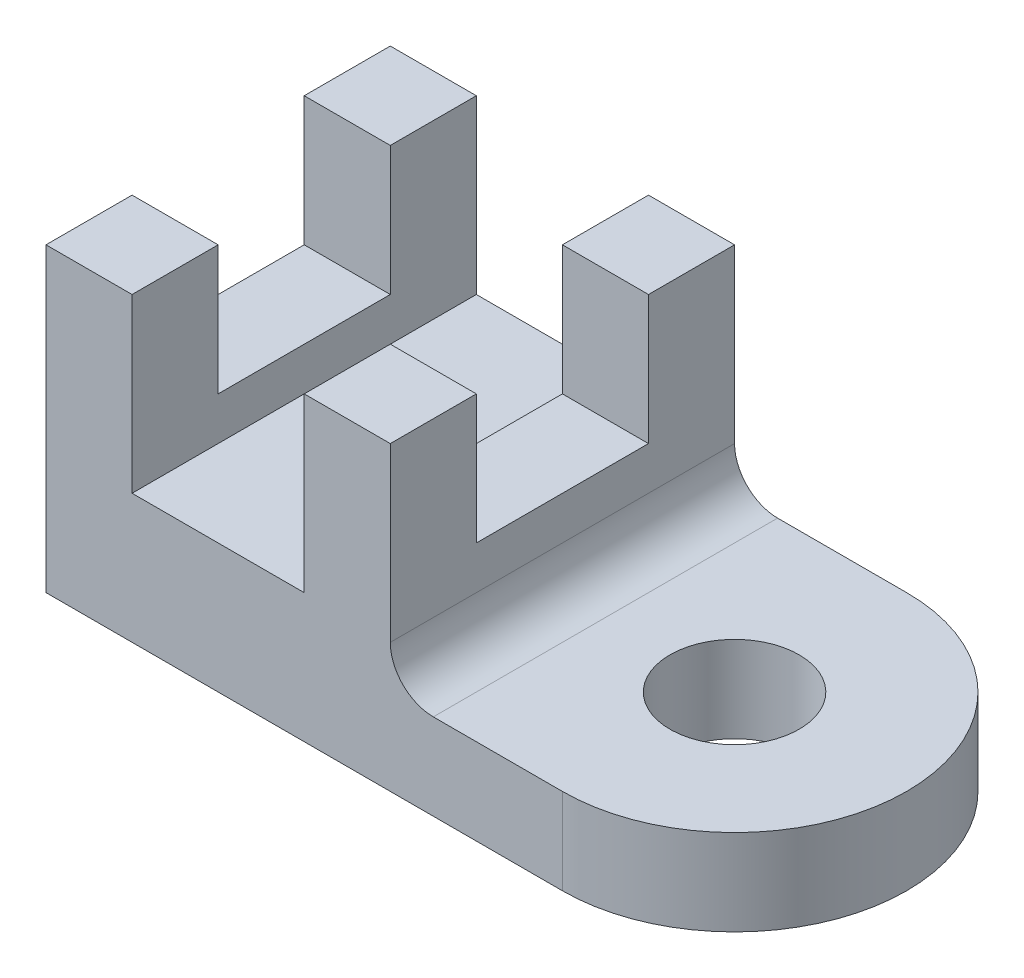
SolidWorks part; units mm, degrees
ref_plane "Front Plane" through (0, 0, 0) normal (0, 0, 1) x (1, 0, 0)
ref_plane "Top Plane" through (0, 0, 0) normal (0, 1, 0) x (1, 0, 0)
ref_plane "Right Plane" through (0, 0, 0) normal (1, 0, 0) x (0, 0, -1)
sketch "Sketch1" plane through (0, 0, 0) normal (0, 0, 1) x (1, 0, 0)
  line L0 (0, 0) -> (76.2, 0)
  line L1 (76.2, 0) -> (76.2, 12.7)
  line L2 (76.2, 12.7) -> (50.8, 12.7)
  line L3 (50.8, 12.7) -> (50.8, 44.45)
  line L4 (50.8, 44.45) -> (38.1, 44.45)
  line L5 (38.1, 44.45) -> (38.1, 19.05)
  line L6 (38.1, 19.05) -> (12.7, 19.05)
  line L7 (12.7, 19.05) -> (12.7, 44.45)
  line L8 (12.7, 44.45) -> (0, 44.45)
  line L9 (0, 44.45) -> (0, 0)
  dimension "D1" = 76.2
  dimension "D2" = 44.45
  dimension "D3" = 12.7
  dimension "D4" = 12.7
  dimension "D5" = 12.7
  dimension "D6" = 19.05
  dimension "D7" = 50.8
  dimension "D8" = 44.45
extrude "base" add sketch "Sketch1" along normal mid plane 50.8
sketch "Sketch2" plane through (0, 0, 0) normal (0, -1, 0) x (1, 0, 0)
  line L1 (76.2, 25.4) -> (76.2, -25.4) construction
  circle A1 centre (76.2, 0) radius 25.4
extrude "circular end " add sketch "Sketch2" against normal up to surface (12.7 mm away) up to face at (63.5, 12.7, 0)
sketch "Sketch3" plane through (0, 12.7, 0) normal (0, 1, 0) x (1, 0, 0)
  circle A0 centre (76.2, 0) radius 9.525
  dimension "D1" = 19.05
extrude "hole " cut sketch "Sketch3" against normal through all
sketch "Sketch4" plane through (50.8, 0, 0) normal (1, 0, 0) x (0, 0, -1)
  line L0 (-25.4, 44.45) -> (25.4, 44.45) construction
  line L1 (-12.7, 44.45) -> (12.7, 44.45)
  line L2 (-12.7, 44.45) -> (-12.7, 25.4)
  line L3 (-12.7, 25.4) -> (12.7, 25.4)
  line L4 (12.7, 44.45) -> (12.7, 25.4)
  line L5 (-25.4, 12.7) -> (-25.4, 44.45) construction
  dimension "D1" = 12.7
  dimension "D2" = 19.05
  dimension "D3" = 25.4
extrude "rectangle cut " cut sketch "Sketch4" against normal through all
fillet "Fillet1" radius 6.35 1 edges at (50.8, 12.7, 0)
